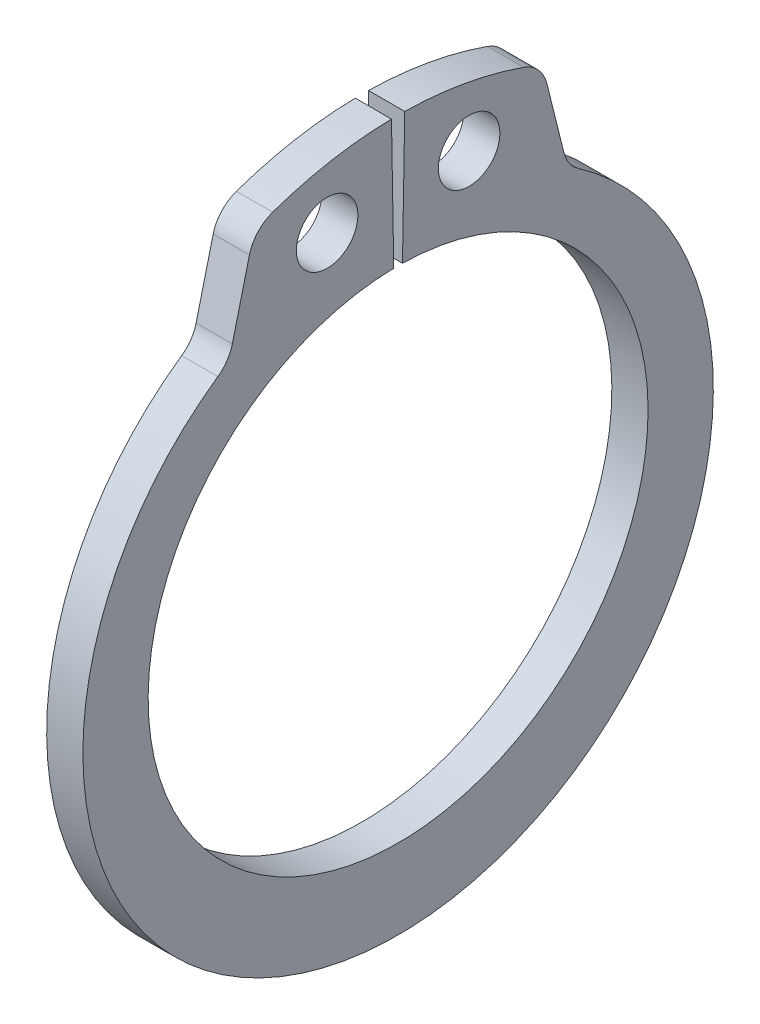
SolidWorks part; units mm, degrees
ref_plane "Front" through (0, 0, 0) normal (0, 0, 1) x (1, 0, 0)
ref_plane "Top" through (0, 0, 0) normal (0, 1, 0) x (1, 0, 0)
ref_plane "Right" through (0, 0, 0) normal (1, 0, 0) x (0, 0, -1)
sketch "Sketch1" plane through (0, 0, 0) normal (1, 0, 0) x (0, 0, -1)
  line L0 (0, 0) -> (0, 6.9) construction
  line L1 (-0.1204, 6.8989) -> (-0.1833, 10.4984)
  line L2 (-0.1833, 10.4984) -> (-3.7988, 10.4353) construction
  line L3 (-3.7988, 10.4353) -> (-4.6698, 6.9422) construction
  line L4 (0.1833, 10.4984) -> (0.1204, 6.8989)
  line L5 (0.1833, 10.4984) -> (3.7988, 10.4353) construction
  line L6 (3.7988, 10.4353) -> (4.6698, 6.9422) construction
  line L7 (-4.6698, 6.9422) -> (-3.8512, 5.7253) construction
  line L8 (4.6698, 6.9422) -> (3.8512, 5.7253) construction
  line L9 (0, -6.9) -> (0, -9.1) construction
  line L10 (-3.7988, 10.4353) -> (-0.1204, 6.8989) construction
  line L12 (0, 6.9) -> (0, 10.5) construction
  line L13 (3.9778, 9.7173) -> (4.6698, 6.9422)
  line L14 (-3.9778, 9.7173) -> (-4.6698, 6.9422)
  circle A0 centre (0, 0) radius 6.9 construction
  arc A1 (-0.1204, 6.8989) -> (0.1204, 6.8989) centre (0, 0) ccw
  circle A2 centre (0, -0.3992) radius 8.7008 construction
  circle A4 centre (-1.9596, 8.6671) radius 0.85
  circle A5 centre (1.9596, 8.6671) radius 0.85
  arc A6 (-4.6698, 6.9422) -> (4.6698, 6.9422) centre (0, -0.3992) ccw
  arc A7 (0.1833, 10.4984) -> (3.9778, 9.7173) centre (0, 0) cw
  arc A8 (-0.1833, 10.4984) -> (-3.9778, 9.7173) centre (0, 0) ccw
  dimension "A" = 13.8
  dimension "Hole" = 1.7
  dimension "Smin" = 1.4667
  dimension "D1" = 75
  dimension "Angle" = 1
  dimension "H" = 3.6
extrude "Extrude1" add sketch "Sketch1" along normal mid plane 1
fillet "Fillet1" radius 1 4 edges at (0, 6.9422, 4.6698) (0, 9.7173, 3.9778) (0, 9.7173, -3.9778) (0, 6.9422, -4.6698)
sketch "Sketch2" plane through (0, 0, 0) normal (0, 0, 1) x (1, 0, 0)
  line L0 (-2.75, 0) -> (8.25, 0)
  line L1 (8.25, 0) -> (8.25, -7.5)
  line L2 (-2.75, 0) -> (-2.75, -7.15)
  line L3 (8.25, -7.5) -> (0.55, -7.5)
  line L4 (0.55, -7.5) -> (0.55, -7.15)
  line L5 (0.55, -7.15) -> (-0.55, -7.15)
  line L6 (-0.55, -7.15) -> (-0.55, -7.5)
  line L7 (-0.55, -7.5) -> (-2.75, -7.5) construction
  line L8 (-2.75, -7.5) -> (-2.75, 0) construction
  line L9 (0, -7.15) -> (0, 0) construction
  line L10 (8.25, 0) -> (14.0551, 0) construction
  line L11 (-2.75, -7.15) -> (-2.4, -7.5)
  line L12 (-2.4, -7.5) -> (-0.55, -7.5)
  dimension "D2" = 11
  dimension "D3" = 2.75
  dimension "D1" = 45
revolve "Revolve1" [suppressed] add sketch "Sketch2" angle 360 about L10
equation "\"D2@Sketch2\" = \"W@Sketch2\"*10"
equation "\"D3@Sketch2\" = \"D2@Sketch2\"/4"
equation "\"Smin@Sketch1\" = \"Smax@Sketch1\"/1.5"
equation "\"D1@Fillet1\" = \"D1@Extrude1\""
